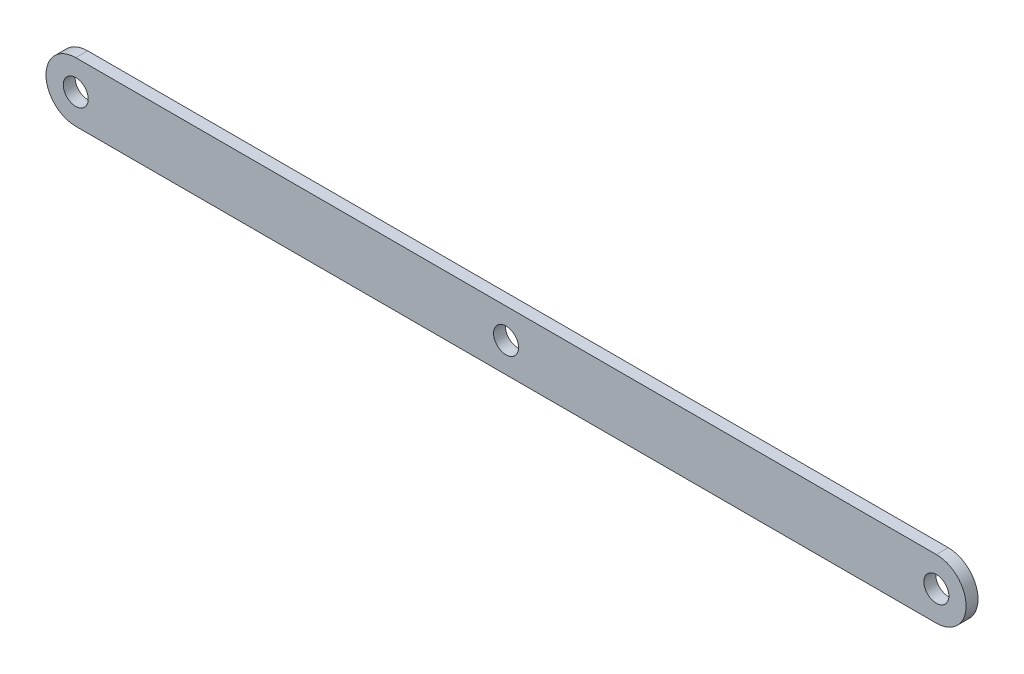
SolidWorks part; units mm, degrees
ref_plane "Vorne" through (0, 0, 0) normal (0, 0, 1) x (1, 0, 0)
ref_plane "Oben" through (0, 0, 0) normal (0, 1, 0) x (1, 0, 0)
ref_plane "Seite" through (0, 0, 0) normal (1, 0, 0) x (0, 0, -1)
sketch "Skizze2" plane through (0, 0, 0) normal (0, 0, 1) x (1, 0, 0)
  line L0 (50, 0) -> (-50, 0) construction
  line L1 (-72.34, 5) -> (72.34, 5)
  line L2 (-72.34, -5) -> (72.34, -5)
  line L3 (0, 5) -> (0, -5) construction
  arc A0 (-72.34, 5) -> (-72.34, -5) centre (-72.34, 0) ccw
  arc A1 (72.34, -5) -> (72.34, 5) centre (72.34, 0) ccw
  circle A2 centre (-72.34, 0) radius 2.1
  circle A3 centre (72.34, 0) radius 2.1
  circle A4 centre (0, 0) radius 2.1
  dimension "D1" = 4.2
  dimension "D2" = 144.68
  dimension "D3" = 10
extrude "Aufsatz-Linear austragen1" add sketch "Skizze2" along normal blind 2
